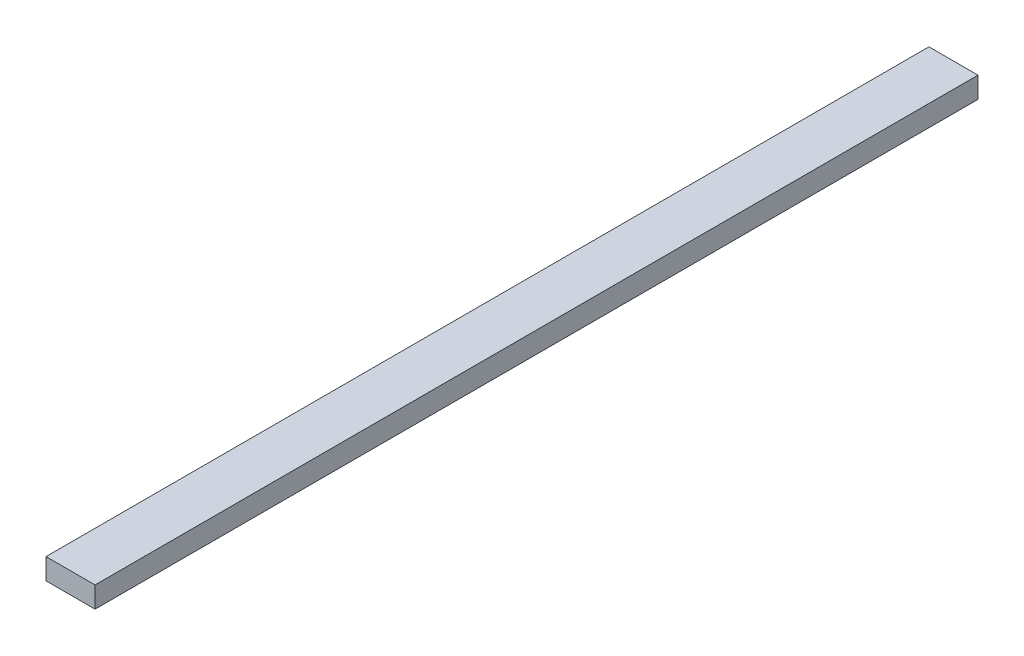
SolidWorks part; units mm, degrees
material "Pine"
ref_plane "Front Plane" through (0, 0, 0) normal (0, 0, 1) x (1, 0, 0)
ref_plane "Top Plane" through (0, 0, 0) normal (0, 1, 0) x (1, 0, 0)
ref_plane "Right Plane" through (0, 0, 0) normal (1, 0, 0) x (0, 0, -1)
sketch "Sketch1" plane through (0, 0, 0) normal (0, 0, 1) x (1, 0, 0)
  line L1 (0, 0) -> (88.9, 0)
  line L2 (0, 0) -> (0, -38.1)
  line L3 (0, -38.1) -> (88.9, -38.1)
  line L4 (88.9, 0) -> (88.9, -38.1)
  dimension "D1" = 88.9
  dimension "D2" = 38.1
extrude "Boss-Extrude1" add sketch "Sketch1" along normal blind 1600.2
equation "\"D1@Boss-Extrude1\"=\"BottomSupportLength\""
equation "\"TableFrontWidth\"=48"
equation "\"TableSideWidth\"=66"
equation "\"LegWidth\"=3.5"
equation "\"LegHeight\"=30"
equation "\"LegDistToBottomStretcher\"=7"
equation "\"BottomStretcherLength\"=\"TableFrontWidth\""
equation "\"SideStretcherLength\"=\"TableSideWidth\"-3"
equation "\"BottomSupportLength\"=\"TableSideWidth\"-3"
equation "\"BottomPlywoodFrontDim\"=\"TableFrontWidth\"-\"LegWidth\"*2-3"
equation "\"BottomPlywoodSideDim\"=\"BottomSupportLength\""
equation "\"TotalBottomSupports\"=4"
equation "\"TotalBottomSupportsLessOne\"=\"TotalBottomSupports\"-1"
equation "\"TotalTopSupports\"=5"
equation "\"TotalTopSupportsLessOne\"=\"TotalTopSupports\"-1"
equation "\"TopSupportSpread\"=\"TableFrontWidth\"-1.5"
equation "\"DistBetweenTopSupports\"=\"TopSupportSpread\"/\"TotalTopSupportsLessOne\""
equation "\"BottomSupportSpread\"= \"BottomPlywoodFrontDim\" - 1.5"
equation "\"DistBetweenBottomSupports\"=\"BottomSupportSpread\"/\"TotalBottomSupportsLessOne\""
